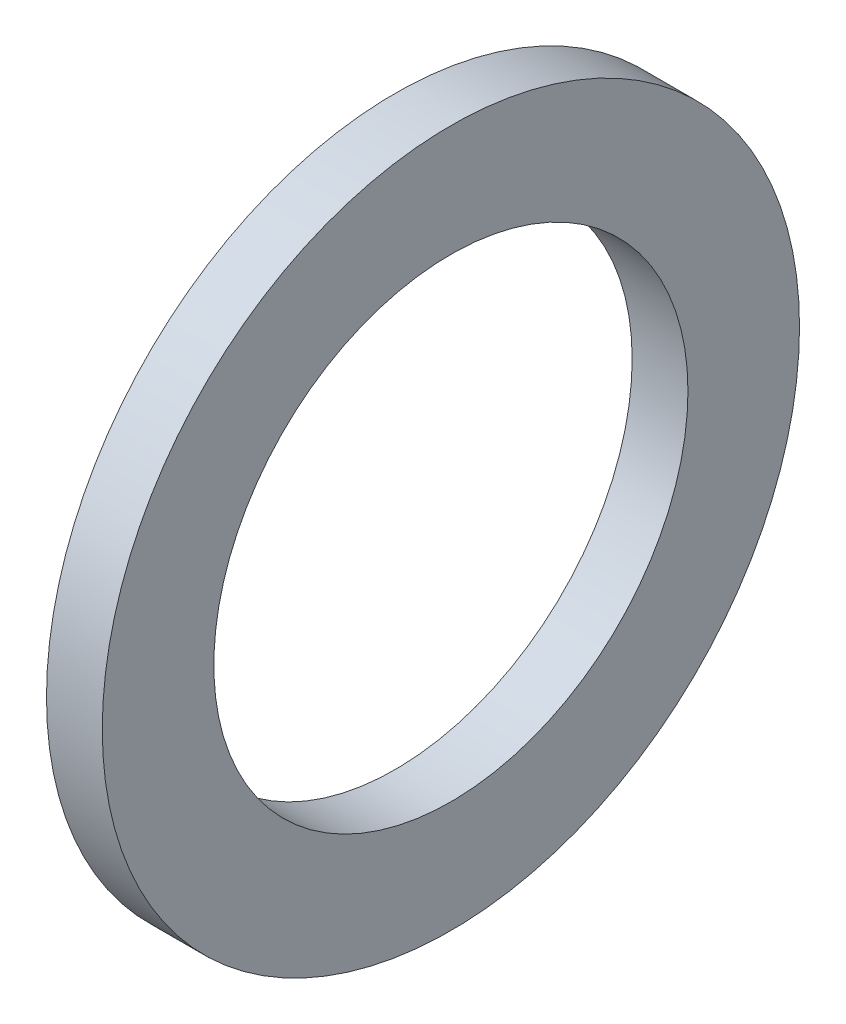
SolidWorks part; units mm, degrees
ref_plane "前视基准面" through (0, 0, 0) normal (0, 0, 1) x (1, 0, 0)
ref_plane "上视基准面" through (0, 0, 0) normal (0, 1, 0) x (1, 0, 0)
ref_plane "右视基准面" through (0, 0, 0) normal (1, 0, 0) x (0, 0, -1)
other "Configuration Table"
sketch "草图1" plane through (0, 0, 0) normal (0, 0, 1) x (1, 0, 0)
  line L0 (0, 0) -> (-20.7826, 0) construction
  line L1 (0, 8.5) -> (0, 12.5)
  line L2 (0, 12.5) -> (2, 12.5)
  line L3 (2, 12.5) -> (2, 8.5)
  line L4 (2, 8.5) -> (0, 8.5)
  dimension "D1" = 2
  dimension "D2" = 8.5
  dimension "D3" = 12.5
revolve "旋转1" add sketch "草图1" angle 360 about L0
